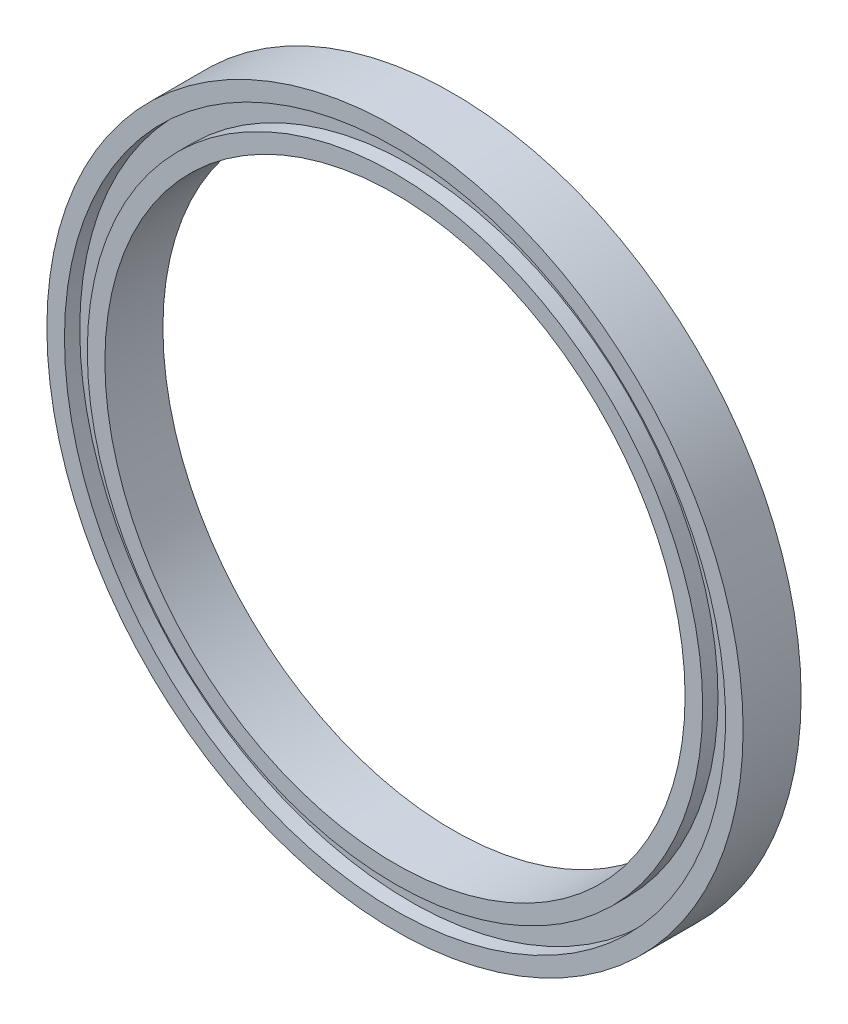
SolidWorks part; units mm, degrees
material "GCr15"
ref_plane "前视基准面" through (0, 0, 0) normal (0, 0, 1) x (1, 0, 0)
ref_plane "上视基准面" through (0, 0, 0) normal (0, 1, 0) x (1, 0, 0)
ref_plane "右视基准面" through (0, 0, 0) normal (1, 0, 0) x (0, 0, -1)
sketch "草图1" plane through (0, 0, 0) normal (1, 0, 0) x (0, 0, -1)
  line L0 (0, 40.0245) -> (0, 0) construction
  line L1 (0, 0) -> (-19.4628, 0) construction
  line L2 (7.6197, 34.925) -> (-15.6509, 34.925) construction
  line L3 (-3.175, 38.1) -> (3.175, 38.1)
  line L4 (3.175, 38.1) -> (3.175, 36.175)
  line L5 (3.175, 36.175) -> (1.5, 36.175)
  line L6 (1.5, 36.175) -> (1.5, 33.675)
  line L7 (3.175, 33.675) -> (1.5, 33.675)
  line L8 (3.175, 31.75) -> (3.175, 33.675)
  line L9 (-3.175, 31.75) -> (3.175, 31.75)
  line L10 (-3.175, 31.75) -> (-3.175, 33.675)
  line L11 (-3.175, 33.675) -> (-1.5, 33.675)
  line L12 (-1.5, 36.175) -> (-1.5, 33.675)
  line L13 (-3.175, 36.175) -> (-1.5, 36.175)
  line L14 (-3.175, 38.1) -> (-3.175, 36.175)
  point P12 (1.5, 34.925)
  point P15 (-1.5, 34.925)
  point P17 (0, 31.75)
  point P22 (0, 38.1)
  dimension "D1" = 63.5
  dimension "D2" = 76.2
  dimension "D3" = 6.35
  dimension "D4" = 2.5
  dimension "D5" = 3
revolve "旋转1" add sketch "草图1" angle 360 about L1
